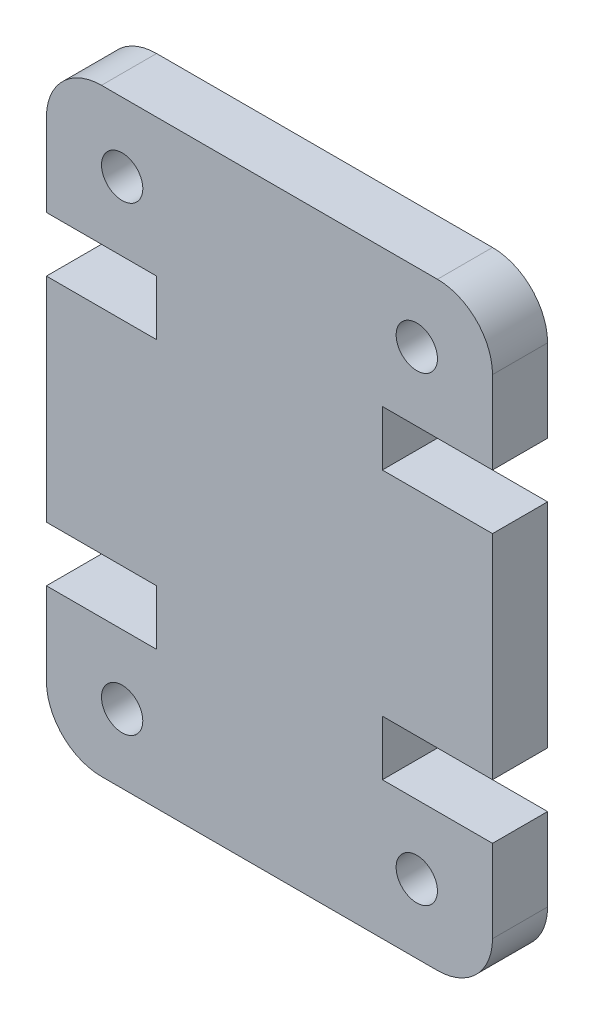
SolidWorks part; units mm, degrees
ref_plane "Front Plane" through (0, 0, 0) normal (0, 0, 1) x (1, 0, 0)
ref_plane "Top Plane" through (0, 0, 0) normal (0, 1, 0) x (1, 0, 0)
ref_plane "Right Plane" through (0, 0, 0) normal (1, 0, 0) x (0, 0, -1)
sketch "Sketch1" plane through (0, 0, 0) normal (0, 0, 1) x (1, 0, 0)
  line L0 (0, 14.74) -> (0, 7)
  line L1 (16.2, 2) -> (16.2, 5)
  line L2 (12.2, 5) -> (16.2, 5)
  line L3 (2, 0) -> (14.2, 0)
  line L4 (16.2, 7) -> (12.2, 7)
  line L5 (12.2, 7) -> (12.2, 5)
  line L6 (16.2, 14.74) -> (16.2, 7)
  line L7 (4, 7) -> (4, 5)
  line L8 (0, 19.74) -> (0, 16.74)
  line L9 (4, 16.74) -> (0, 16.74)
  line L10 (0, 7) -> (4, 7)
  line L11 (0, 14.74) -> (4, 14.74)
  line L12 (4, 5) -> (0, 5)
  line L13 (4, 14.74) -> (4, 16.74)
  line L14 (12.2, 14.74) -> (12.2, 16.74)
  line L15 (16.2, 14.74) -> (12.2, 14.74)
  line L16 (0, 2) -> (0, 5)
  line L17 (2, 21.74) -> (14.2, 21.74)
  line L18 (12.2, 16.74) -> (16.2, 16.74)
  line L19 (16.2, 19.74) -> (16.2, 16.74)
  line L20 (8.1, 21.74) -> (8.1, 0) construction
  line L21 (0, 10.87) -> (16.2, 10.87) construction
  circle A0 centre (13.45, 2.5) radius 0.75
  arc A1 (16.2, 2) -> (14.2, 0) centre (14.2, 2) cw
  circle A2 centre (2.75, 19.24) radius 0.75
  arc A3 (0, 2) -> (2, 0) centre (2, 2) ccw
  arc A4 (0, 19.74) -> (2, 21.74) centre (2, 19.74) cw
  circle A5 centre (2.75, 2.5) radius 0.75
  arc A6 (16.2, 19.74) -> (14.2, 21.74) centre (14.2, 19.74) ccw
  circle A7 centre (13.45, 19.24) radius 0.75
  point P15 (8.1, 10.87)
  dimension "D1" = 1.5
  dimension "D2" = 2
  dimension "D3" = 2.75
  dimension "D4" = 8.1
  dimension "D5" = 2.5
  dimension "D6" = 5
  dimension "D8" = 10.87
extrude "Boss-Extrude1" add sketch "Sketch1" along normal blind 4
sketch "Sketch2" plane through (0, 0, 0) normal (0, 0, -1) x (-1, 0, 0)
  line L0 (0, 0) -> (-16.2, 0)
  line L1 (-16.2, 0) -> (-16.2, 21.74)
  line L2 (-16.2, 21.74) -> (0, 21.74)
  line L3 (0, 21.74) -> (0, 0)
extrude "Cut-Extrude1" cut sketch "Sketch2" against normal blind 2
equation "\"D4@Sketch1\"= \"fingerWidth@parametersSketch@prostheticParameters.SLDPRT\" / 2'PIP width"
equation "\"D8@Sketch1\"= ( \"HL@parametersSketch@prostheticParameters.SLDPRT\" * 0.204 - 4 - 12 ) / 2 'PIP length - Sil. Sht MIP - Sil.Sht PIP"
